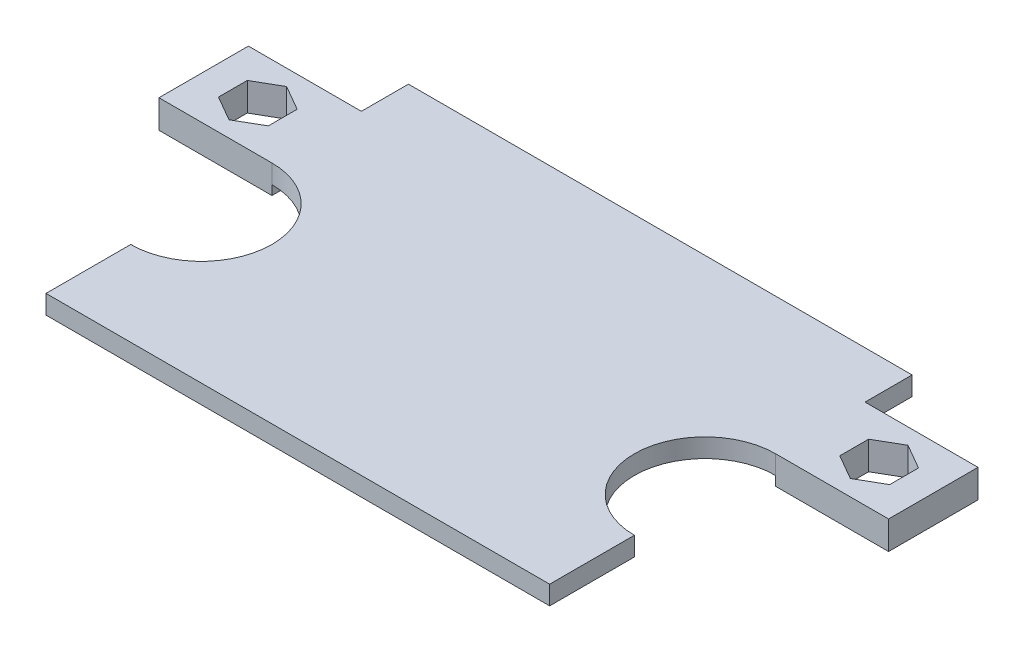
SolidWorks part; units mm, degrees
ref_plane "Front Plane" through (0, 0, 0) normal (0, 0, 1) x (1, 0, 0)
ref_plane "Top Plane" through (0, 0, 0) normal (0, 1, 0) x (1, 0, 0)
ref_plane "Right Plane" through (0, 0, 0) normal (1, 0, 0) x (0, 0, -1)
sketch "Sketch1" plane through (0, 0, 0) normal (0, 1, 0) x (1, 0, 0)
  line L1 (26.75, 19.25) -> (-26.75, 19.25)
  line L2 (26.75, 19.25) -> (26.75, -19.25)
  line L3 (26.75, -19.25) -> (-26.75, -19.25)
  line L4 (-26.75, 19.25) -> (-26.75, -19.25)
  line L5 (26.75, 19.25) -> (-26.75, -19.25) construction
  line L6 (26.75, -19.25) -> (-26.75, 19.25) construction
  line L7 (-27, -19.5) -> (27, -19.5)
  line L8 (-27, -19.5) -> (-27, 19.5)
  line L9 (-27, 19.5) -> (27, 19.5)
  line L10 (27, -19.5) -> (27, 19.5)
  line L11 (-27, -19.5) -> (27, 19.5) construction
  line L12 (-27, 19.5) -> (27, -19.5) construction
  point P0 (0, 0)
  point P6 (0, 0)
  dimension "D1" = 53.5
  dimension "D2" = 38.5
  dimension "D3" = 54
  dimension "D4" = 39
extrude "Boss-Extrude1" add sketch "Sketch1" against normal blind 2 contours L4 L3 L2 L1
sketch "Sketch2" plane through (0, 0, 0) normal (0, 1, 0) x (1, 0, 0)
  line L0 (-27, -19.5) -> (-27, 4.5) construction
  line L5 (27, 19.5) -> (-27, -19.5) construction
  line L6 (27, -19.5) -> (-27, 19.5) construction
  line L7 (-27, 4.5) -> (-39, 4.5) construction
  line L8 (-39, 4.5) -> (-39, 14.5) construction
  line L9 (-39, 14.5) -> (-27, 14.5) construction
  line L10 (0, 19.25) -> (0, -19.25) construction
  line L11 (-38.75, 4.75) -> (-26.75, 4.75)
  line L12 (-33, 6.44) -> (-30.35, 7.97)
  line L13 (-30.35, 7.97) -> (-30.35, 11.03)
  line L14 (-30.35, 11.03) -> (-33, 12.56)
  line L15 (-33, 12.56) -> (-35.65, 11.03)
  line L16 (-35.65, 11.03) -> (-35.65, 7.97)
  line L17 (-35.65, 7.97) -> (-33, 6.44)
  line L18 (-38.75, 4.75) -> (-38.75, 14.25)
  line L19 (-38.75, 14.25) -> (-26.75, 14.25)
  line L20 (-26.75, 14.25) -> (-26.75, 4.75)
  line L21 (-26.75, 19.25) -> (-26.75, -19.25) construction
  line L22 (26.75, 19.25) -> (-26.75, 19.25) construction
  line L23 (26.75, -19.25) -> (-26.75, -19.25) construction
  line L24 (-26.75, 19.25) -> (-26.75, 14.25) construction
  line L25 (26.75, 19.25) -> (-26.75, 19.25) construction
  line L26 (26.75, -19.25) -> (-27, -19.25) construction
  line L27 (26.75, 19.25) -> (26.75, -19.25) construction
  line L28 (-27, 4.75) -> (-38.75, 4.75) construction
  line L29 (-27, 19.5) -> (-27, 14.5) construction
  line L30 (27, 19.5) -> (-27, 19.5) construction
  line L31 (27, 19.5) -> (27, -19.5) construction
  line L32 (27, -19.5) -> (-27, -19.5) construction
  line L33 (38.75, 4.75) -> (38.75, 14.25)
  line L34 (38.75, 14.25) -> (26.75, 14.25)
  line L35 (26.75, 14.25) -> (26.75, 4.75)
  line L36 (38.75, 4.75) -> (26.75, 4.75)
  line L37 (35.65, 7.97) -> (33, 6.44)
  line L38 (35.65, 11.03) -> (35.65, 7.97)
  line L39 (33, 12.56) -> (35.65, 11.03)
  line L40 (30.35, 11.03) -> (33, 12.56)
  line L41 (30.35, 7.97) -> (30.35, 11.03)
  line L42 (33, 6.44) -> (30.35, 7.97)
  circle A0 centre (-33, 9.5) radius 2.65 construction
  circle A1 centre (33, 9.5) radius 2.65 construction
  point P0 (0, 0)
  dimension "D4" = 5
  dimension "D6" = 5.3
  dimension "D1" = 54
  dimension "D2" = 39
  dimension "D3" = 24
  dimension "D5" = 6
  dimension "D7" = 0.25
extrude "Boss-Extrude2" add sketch "Sketch2" against normal blind 3
sketch "Sketch3" plane through (0, 0, 0) normal (0, 1, 0) x (1, 0, 0)
  line L0 (-26.75, 4.75) -> (-26.75, -19.25) construction
  line L1 (0, 19.25) -> (0, -19.25) construction
  line L2 (26.75, 19.25) -> (-26.75, 19.25) construction
  line L3 (26.75, -19.25) -> (-26.75, -19.25) construction
  line L4 (-26.75, 4.75) -> (-26.75, -10.25)
  line L5 (26.75, 4.75) -> (26.75, -10.25)
  arc A0 (-26.75, 4.75) -> (-26.75, -10.25) centre (-26.75, -2.75) cw
  arc A1 (26.75, 4.75) -> (26.75, -10.25) centre (26.75, -2.75) ccw
  dimension "D1" = 15
extrude "Cut-Extrude1" cut sketch "Sketch3" against normal blind 2
